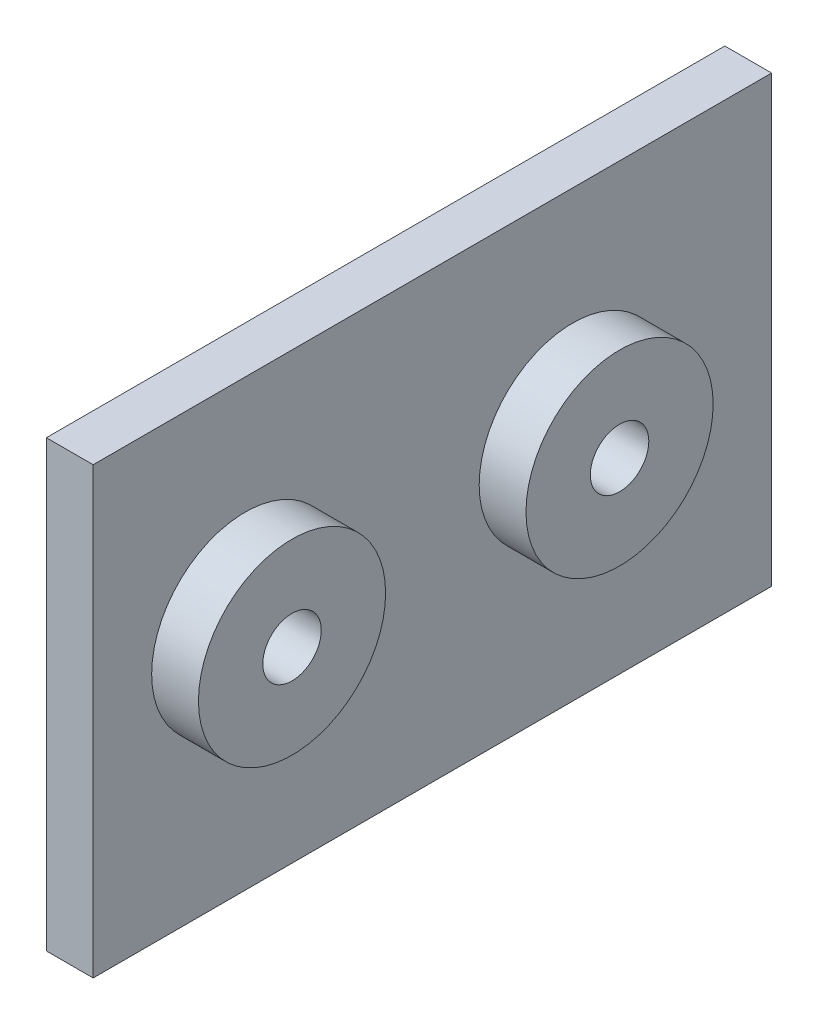
SolidWorks part; units mm, degrees
ref_plane "Plano frontal" through (0, 0, 0) normal (0, 0, 1) x (1, 0, 0)
ref_plane "Plano superior" through (0, 0, 0) normal (0, 1, 0) x (1, 0, 0)
ref_plane "Plano direito" through (0, 0, 0) normal (1, 0, 0) x (0, 0, -1)
sketch "Esboço1" plane through (0, 0, 0) normal (1, 0, 0) x (0, 0, -1)
  line L1 (-12.4269, 9.0019) -> (16.5731, 9.0019)
  line L2 (-12.4269, 9.0019) -> (-12.4269, -9.9981)
  line L3 (-12.4269, -9.9981) -> (16.5731, -9.9981)
  line L4 (16.5731, 9.0019) -> (16.5731, -9.9981)
  circle A0 centre (8.0731, 0.0019) radius 1.25
  circle A1 centre (-5.9269, 0.0019) radius 1.25
  point P11 (4.1926, -3.3448)
  dimension "D5" = 2.5
  dimension "D6" = 2.5
  dimension "D3" = 9
  dimension "D7" = 5.9269
  dimension "D9" = 8.5
  dimension "D1" = 29
  dimension "D2" = 19
  dimension "D4" = 14
  dimension "D8" = 8.0731
extrude "Ressalto-extrusão1" add sketch "Esboço1" along normal blind 2
sketch "Esboço2" plane through (2, 0, 0) normal (1, 0, 0) x (0, 0, -1)
  line L0 (16.5731, -9.9981) -> (16.5731, 9.0019) construction
  circle A0 centre (8.0731, 0) radius 4
  circle A1 centre (-5.9269, 0) radius 4
  circle A2 centre (-5.9269, 0) radius 1.25
  circle A3 centre (8.0731, 0) radius 1.25
  dimension "D1" = 8
  dimension "D2" = 8.5
  dimension "D3" = 8
  dimension "D4" = 14
  dimension "D6" = 5.9269
  dimension "D7" = 2.5
  dimension "D8" = 2.5
  dimension "D5" = 8.0731
extrude "Ressalto-extrusão2" add sketch "Esboço2" along normal blind 2
